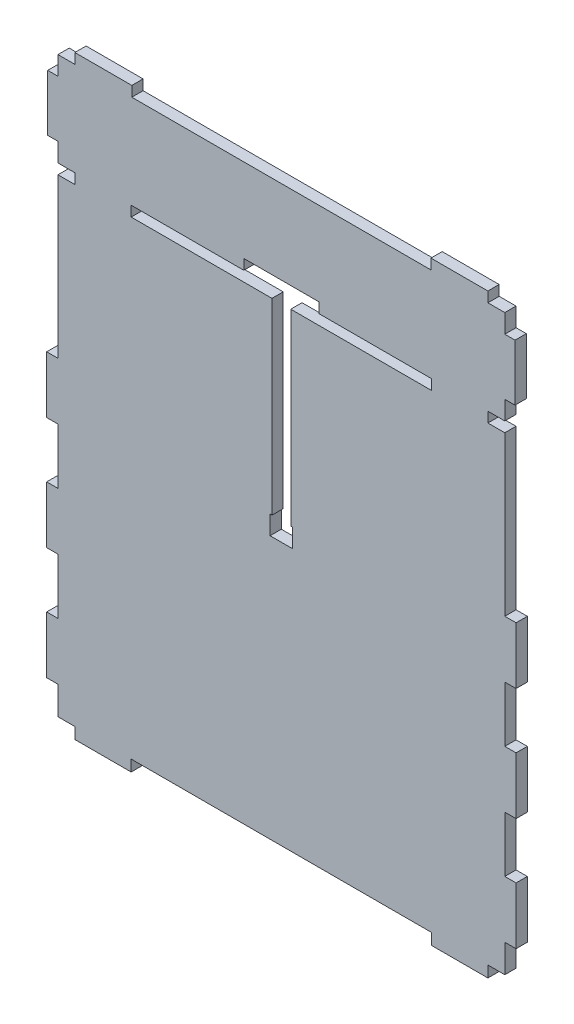
SolidWorks part; units mm, degrees
ref_plane "Спереди" through (0, 0, 0) normal (0, 0, 1) x (1, 0, 0)
ref_plane "Сверху" through (0, 0, 0) normal (0, 1, 0) x (1, 0, 0)
ref_plane "Справа" through (0, 0, 0) normal (1, 0, 0) x (0, 0, -1)
other "Configuration Table"
sketch "Эскиз2" plane through (0, 0, 0) normal (0, 0, 1) x (1, 0, 0)
  line L0 (-119, 55.45) -> (-119, -250) construction
  line L1 (0, 0) -> (-9, 0)
  line L2 (6, -144.65) -> (6, -175)
  line L3 (0, -250) -> (-9, -250)
  line L4 (-244, -144.65) -> (-244, -175)
  line L5 (-9, -256) -> (-39, -256)
  line L7 (-229, -250) -> (-229, -256)
  line L8 (-229, -256) -> (-199, -256)
  line L16 (-9, -250) -> (-9, -256)
  line L17 (-229, -250) -> (-238, -250)
  line L20 (6, -235) -> (0, -235)
  line L23 (-244, -235) -> (-238, -235)
  line L24 (-238, -250) -> (-238, -235)
  line L25 (-238, -204.65) -> (-244, -204.65)
  line L26 (-238, -204.65) -> (-238, -175)
  line L27 (-238, -175) -> (-244, -175)
  line L29 (-244, -144.65) -> (-238, -144.65)
  line L32 (-238, -144.65) -> (-238, -115)
  line L33 (0, -250) -> (0, -235)
  line L36 (0, -175) -> (6, -175)
  line L38 (0, -204.65) -> (6, -204.65)
  line L39 (0, -204.65) -> (0, -175)
  line L41 (0, -144.65) -> (0, -115)
  line L42 (6, -144.65) -> (0, -144.65)
  line L44 (-244, -204.65) -> (-244, -235)
  line L45 (6, -204.65) -> (6, -235)
  line L46 (-238, -84.65) -> (-238, 0)
  line L47 (-238, -115) -> (-244, -115)
  line L49 (-238, -84.65) -> (-244, -84.65)
  line L50 (-244, -115) -> (-244, -84.65)
  line L51 (0, -115) -> (6, -115)
  line L52 (6, -115) -> (6, -84.65)
  line L53 (0, -84.65) -> (6, -84.65)
  line L54 (0, -84.65) -> (0, 0)
  line L55 (-229, 0) -> (-238, 0)
  line L58 (-199, -250) -> (-39, -250)
  line L61 (-229, 0) -> (-229, 5.45)
  line L63 (-199, 0) -> (-199, 5.45)
  line L64 (-9, 0) -> (-9, 5.45)
  line L65 (-39, 0) -> (-39, 5.45)
  line L67 (-39, 0) -> (-199, 0)
  line L68 (-199, -250) -> (-199, -256)
  line L69 (-39, -250) -> (-39, -256)
  line L70 (-199, 5.45) -> (-139, 5.45)
  line L71 (-238, 5.45) -> (-229, 5.45)
  line L72 (-238, 5.45) -> (-238, 15.45)
  line L73 (-238, 55.45) -> (-229, 55.45)
  line L74 (0, 5.45) -> (0, 15.45)
  line L75 (-9, 5.45) -> (0, 5.45)
  line L76 (-198.65, 55.45) -> (-39.35, 55.45)
  line L78 (-139, 5.45) -> (-139, 10.9)
  line L79 (-139, 10.9) -> (-99, 10.9)
  line L80 (-99, 5.45) -> (-99, 10.9)
  line L82 (-229, 55.45) -> (-229, 60.9)
  line L83 (-229, 60.9) -> (-198.65, 60.9)
  line L84 (-198.65, 55.45) -> (-198.65, 60.9)
  line L85 (-39.35, 55.45) -> (-39.35, 60.9)
  line L86 (-9, 60.9) -> (-39.35, 60.9)
  line L87 (-9, 55.45) -> (-9, 60.9)
  line L88 (-9, 55.45) -> (0, 55.45)
  line L89 (-99, 5.45) -> (-39, 5.45)
  line L90 (-238, 30.45) -> (0, 30.45) construction
  line L91 (-238, 45.45) -> (-238, 55.45)
  line L92 (-238, 45.45) -> (-243.45, 45.45)
  line L94 (-238, 15.45) -> (-243.45, 15.45)
  line L95 (-243.45, 45.45) -> (-243.45, 15.45)
  line L96 (0, 15.45) -> (5.45, 15.45)
  line L97 (5.45, 45.45) -> (5.45, 15.45)
  line L98 (0, 45.45) -> (5.45, 45.45)
  line L99 (0, 45.45) -> (0, 55.45)
  dimension "D2" = 5.45
  dimension "D3" = 6
  dimension "D4" = 30
  dimension "D5" = 9
  dimension "D6" = 15
  dimension "D7" = 6
  dimension "D8" = 29.65
  dimension "D9" = 30.35
  dimension "D10" = 30.35
  dimension "D11" = 238
  dimension "D12" = 29.65
  dimension "D13" = 9
  dimension "D14" = 160
  dimension "D15" = 256
  dimension "D16" = 50
  dimension "D17" = 30
  dimension "D18" = 5.45
  dimension "D19" = 40
  dimension "D20" = 5.45
  dimension "D21" = 5.45
  dimension "D22" = 30
  dimension "D23" = 25
  dimension "D24" = 30.35
extrude "Бобышка-Вытянуть1" add sketch "Эскиз2" along normal blind 6
sketch "Эскиз4" plane through (0, 0, 6) normal (0, 0, 1) x (1, 0, 0)
  line L0 (-119, 0) -> (-119, -250) construction
  line L1 (-199, 0) -> (-39, 0) construction
  line L2 (-199, -250) -> (-39, -250) construction
  line L3 (-114, -100) -> (-113, -100)
  line L10 (-125, -110) -> (-113, -110)
  line L11 (-125, -110) -> (-125, -100)
  line L12 (-125, -100) -> (-124, -100)
  line L13 (-113, -110) -> (-113, -100)
  line L14 (-124, 0) -> (-114, 0)
  line L15 (-124, 0) -> (-124, -100)
  line L17 (-114, 0) -> (-114, -100)
  dimension "D1" = 5
  dimension "D2" = 10
  dimension "D3" = 12
  dimension "D4" = 100
extrude "Вырез-Вытянуть1" cut sketch "Эскиз4" against normal blind 10
